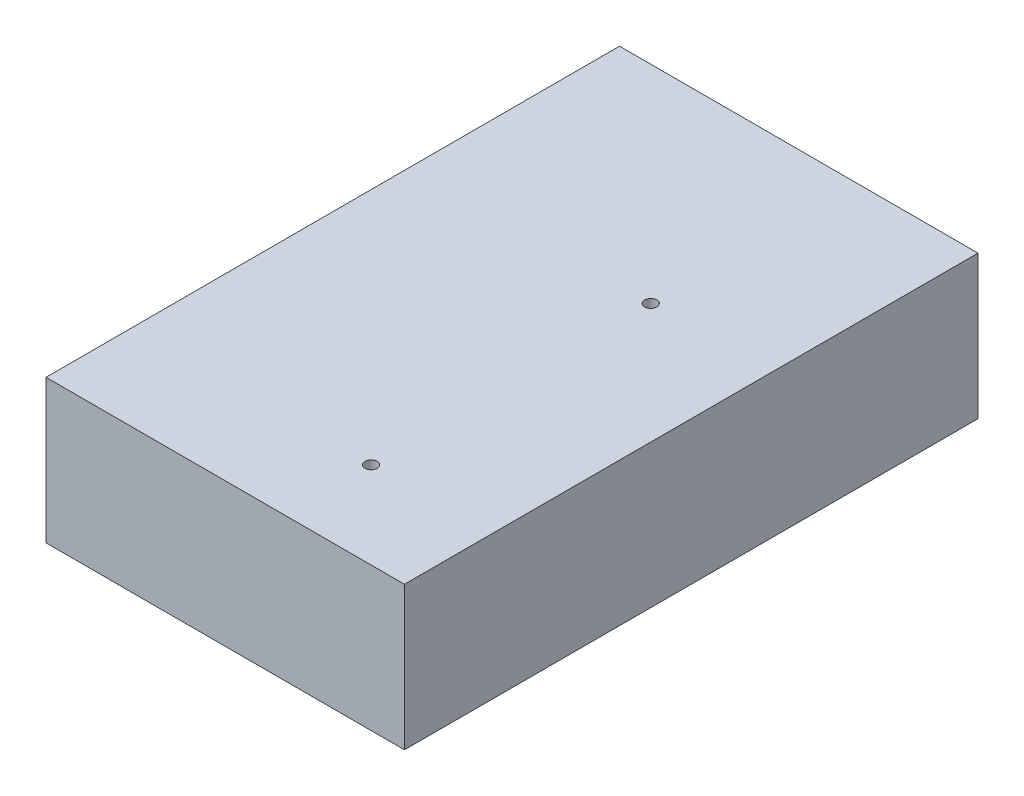
SolidWorks part; units mm, degrees
ref_plane "前视基准面" through (0, 0, 0) normal (0, 0, 1) x (1, 0, 0)
ref_plane "上视基准面" through (0, 0, 0) normal (0, 1, 0) x (1, 0, 0)
ref_plane "右视基准面" through (0, 0, 0) normal (1, 0, 0) x (0, 0, -1)
sketch "草图1" plane through (0, 0, 0) normal (0, 1, 0) x (1, 0, 0)
  line L1 (-50, -80) -> (50, -80)
  line L2 (-50, -80) -> (-50, 80)
  line L3 (-50, 80) -> (50, 80)
  line L4 (50, -80) -> (50, 80)
  line L5 (0, 80) -> (0, -80) construction
  line L6 (-50, 0) -> (50, 0) construction
  point P0 (0, 0)
  dimension "D1" = 100
  dimension "D2" = 160
extrude "凸台-拉伸1" add sketch "草图1" along normal blind 40
sketch "草图2" plane through (0, 0, 0) normal (0, -1, 0) x (1, 0, 0)
  line L0 (-50, 80) -> (50, 80) construction
  line L2 (50, 80) -> (50, -80) construction
  circle A0 centre (16.5, 55.8) radius 1.7
  circle A1 centre (16.5, -22.2) radius 1.7
  dimension "D1" = 3.4
  dimension "D5" = 3.4
  dimension "D2" = 24.2
  dimension "D3" = 33.5
  dimension "D4" = 78
  dimension "D6" = 33.5
extrude "切除-拉伸1" cut sketch "草图2" against normal through all
